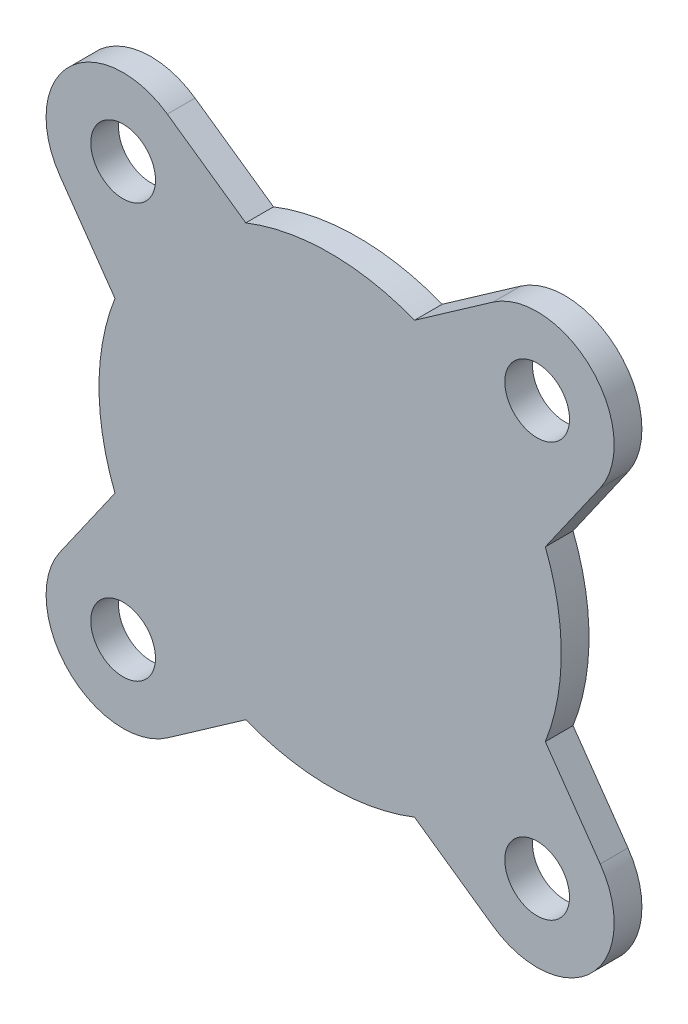
SolidWorks part; units mm, degrees
ref_plane "Спереди" through (0, 0, 0) normal (0, 0, 1) x (1, 0, 0)
ref_plane "Сверху" through (0, 0, 0) normal (0, 1, 0) x (1, 0, 0)
ref_plane "Справа" through (0, 0, 0) normal (1, 0, 0) x (0, 0, -1)
sketch "Эскиз1" plane through (0, 0, 0) normal (0, 0, 1) x (1, 0, 0)
  line L0 (-6.7175, 6.7175) -> (6.7175, -6.7175) construction
  line L1 (6.7175, 6.7175) -> (-6.7175, -6.7175) construction
  line L2 (0, 0) -> (0, 11.5046) construction
  line L3 (8.7654, 5.2836) -> (6.9826, 2.7374)
  line L4 (5.2836, 8.7654) -> (2.7374, 6.9826)
  line L5 (-8.7654, -5.2836) -> (-6.9826, -2.7374)
  line L6 (-5.2836, -8.7654) -> (-2.7374, -6.9826)
  line L7 (-8.7654, 5.2836) -> (-6.9826, 2.7374)
  line L8 (-5.2836, 8.7654) -> (-2.7374, 6.9826)
  line L9 (5.2836, -8.7654) -> (2.7374, -6.9826)
  line L10 (8.7654, -5.2836) -> (6.9826, -2.7374)
  circle A0 centre (6.7175, 6.7175) radius 1.05
  circle A1 centre (-6.7175, 6.7175) radius 1.05
  circle A2 centre (-6.7175, -6.7175) radius 1.05
  circle A3 centre (6.7175, -6.7175) radius 1.05
  circle A4 centre (0, 0) radius 7.5
  circle A5 centre (-6.7175, 6.7175) radius 2.5
  circle A6 centre (6.7175, 6.7175) radius 2.5
  circle A7 centre (6.7175, -6.7175) radius 2.5
  circle A8 centre (-6.7175, -6.7175) radius 2.5
  dimension "D3" = 2.1
  dimension "D4" = 2.1
  dimension "D5" = 2.1
  dimension "D6" = 2.1
  dimension "D8" = 15
  dimension "D9" = 5
  dimension "D10" = 5
  dimension "D11" = 5
  dimension "D12" = 5
  dimension "D1" = 19
  dimension "D2" = 19
  dimension "D7" = 45
  dimension "D13" = 10
extrude "Бобышка-Вытянуть1" add sketch "Эскиз1" along normal blind 0.9 contours A8 A4 A7 A6 A5 | A6 A4 L3 | A4 A6 | A6 A4 A0 | A6 L4 A4 | A5 L7 A4 | A5 A4 L8 | A1 | A4 A8 | A4 A8 A2 | A8 L6 A4 | A8 A4 L5 | A7 A4 L9 | A7 A4 A3 | A7 L10 A4 | A4 A7
